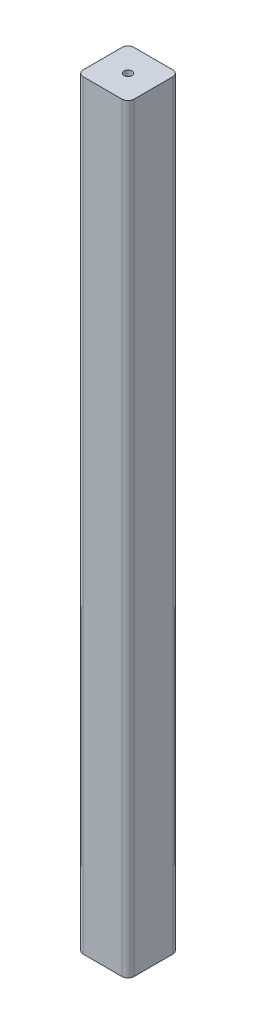
SolidWorks part; units mm, degrees
ref_plane "Front Plane" through (0, 0, 0) normal (0, 0, 1) x (1, 0, 0)
ref_plane "Top Plane" through (0, 0, 0) normal (0, 1, 0) x (1, 0, 0)
ref_plane "Right Plane" through (0, 0, 0) normal (1, 0, 0) x (0, 0, -1)
sketch "Sketch1" plane through (0, 0, 0) normal (0, 1, 0) x (1, 0, 0)
  line L1 (3, 0) -> (22.4, 0)
  line L2 (0, 3) -> (0, 22.4)
  line L3 (3, 25.4) -> (22.4, 25.4)
  line L4 (25.4, 3) -> (25.4, 22.4)
  circle A0 centre (12.7, 12.7) radius 2
  arc A1 (25.4, 22.4) -> (22.4, 25.4) centre (22.4, 22.4) ccw
  arc A2 (22.4, 0) -> (25.4, 3) centre (22.4, 3) ccw
  arc A3 (0, 3) -> (3, 0) centre (3, 3) ccw
  arc A4 (0, 22.4) -> (3, 25.4) centre (3, 22.4) cw
  point P11 (25.4, 0)
  point P14 (0, 0)
  point P17 (0, 25.4)
  dimension "D3" = 3
  dimension "D1" = 25.4
  dimension "D2" = 25.4
extrude "Boss-Extrude1" add sketch "Sketch1" along normal blind 380
